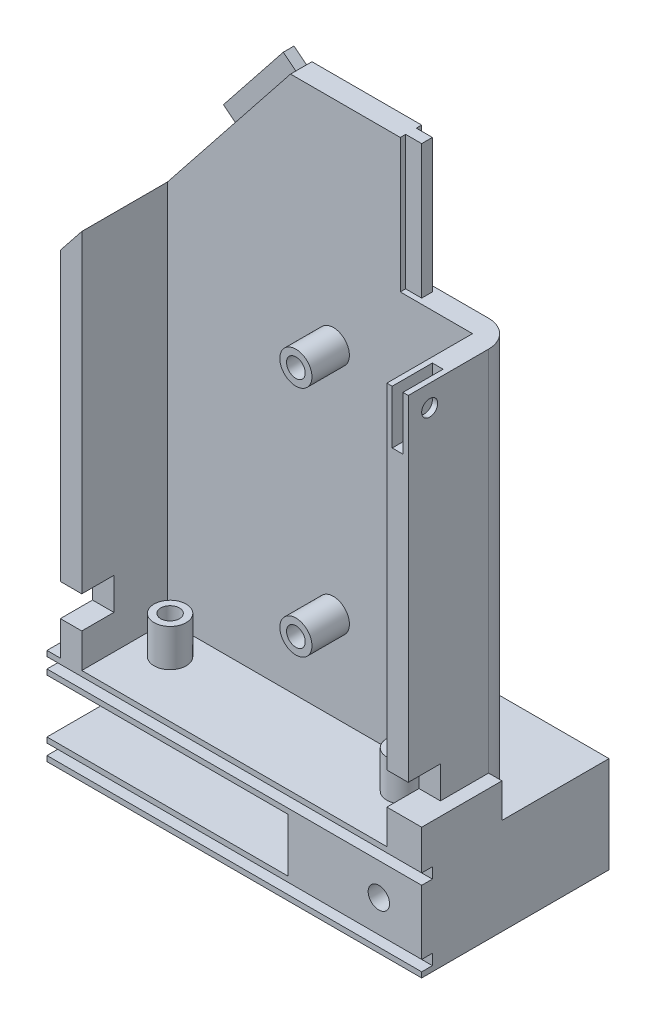
SolidWorks part; units mm, degrees
ref_plane "Front Plane" through (0, 0, 0) normal (0, 0, 1) x (1, 0, 0)
ref_plane "Top Plane" through (0, 0, 0) normal (0, 1, 0) x (1, 0, 0)
ref_plane "Right Plane" through (0, 0, 0) normal (1, 0, 0) x (0, 0, -1)
sketch "Sketch1" plane through (0, 0, 0) normal (0, 1, 0) x (1, 0, 0)
  line L1 (-32.5, -20) -> (32.5, -20)
  line L2 (-32.5, -20) -> (-32.5, 20)
  line L3 (-32.5, 20) -> (32.5, 20)
  line L4 (32.5, -20) -> (32.5, 20)
  line L5 (-32.5, -20) -> (32.5, 20) construction
  line L6 (-32.5, 20) -> (32.5, -20) construction
  point P0 (0, 0)
  dimension "D1" = 65
  dimension "D2" = 40
extrude "Boss-Extrude1" add sketch "Sketch1" along normal blind 100
shell "Shell1" thickness 4
fillet "Fillet1" radius 5 4 edges at (32.5, 50, -20) (32.5, 50, 20) (-32.5, 50, -20) (-32.5, 50, 20)
sketch "Sketch2" plane through (0, 0, 0) normal (0, 0, 1) x (1, 0, 0)
  line L0 (-5.5, 100) -> (-32.5, 66)
  line L1 (28.5, 100) -> (-28.5, 100) construction
  line L2 (-32.5, 100) -> (-32.5, 0) construction
  line L3 (-32.5, 66) -> (-32.5, 100)
  line L4 (-32.5, 100) -> (-5.5, 100)
  dimension "D1" = 5.5
  dimension "D2" = 66
extrude "Cut-Extrude1" cut sketch "Sketch2" against normal through all both and the other way through all
sketch "Sketch3" plane through (0, 0, 0) normal (0, 0, 1) x (1, 0, 0)
  line L1 (32.5, 100) -> (15, 100)
  line L2 (32.5, 100) -> (32.5, 75)
  line L3 (32.5, 75) -> (15, 75)
  line L4 (15, 100) -> (15, 75)
  dimension "D1" = 25
  dimension "D2" = 17.5
extrude "Cut-Extrude2" cut sketch "Sketch3" against normal through all both and the other way through all
sketch "Sketch5" plane through (15, 0, 0) normal (1, 0, 0) x (0, 0, -1)
  line L0 (-18, 100) -> (-18, 75) construction
  line L1 (-16, 100) -> (-20, 100) construction
  line L2 (-16, 75) -> (-20, 75) construction
  line L4 (-19, 100) -> (-17, 100)
  line L5 (-19, 100) -> (-19, 75)
  line L6 (-19, 75) -> (-17, 75)
  line L7 (-17, 100) -> (-17, 75)
  dimension "D1" = 2
extrude "Boss-Extrude2" add sketch "Sketch5" along normal blind 3
mirror "Mirror1" about plane through (0, 0, 0) normal (0, 0, 1) of "Boss-Extrude2"
sketch "Sketch6" plane through (-52.0732, 41.3523, 0) normal (-0.7831, 0.6219, 0) x (0, 0, 1)
  line L0 (-18, 74.8907) -> (-18, 56.8907) construction
  line L1 (-20, 74.8907) -> (-16, 74.8907) construction
  line L3 (-19, 74.8907) -> (-17, 74.8907)
  line L4 (-19, 74.8907) -> (-19, 56.8907)
  line L5 (-19, 56.8907) -> (-17, 56.8907)
  line L6 (-17, 74.8907) -> (-17, 56.8907)
  dimension "D1" = 18
  dimension "D2" = 2
extrude "Boss-Extrude3" add sketch "Sketch6" along normal blind 3
mirror "Mirror2" about plane through (0, 0, 0) normal (0, 0, 1) of "Boss-Extrude3"
sketch "Sketch8" plane through (0, 0, 0) normal (0, 1, 0) x (1, 0, 0)
  line L1 (-35, -35) -> (35, -35)
  line L2 (-35, -35) -> (-35, 35)
  line L3 (-35, 35) -> (35, 35)
  line L4 (35, -35) -> (35, 35)
  line L5 (-35, -35) -> (35, 35) construction
  line L6 (-35, 35) -> (35, -35) construction
  point P0 (0, 0)
  dimension "D1" = 70
  dimension "D2" = 70
extrude "Boss-Extrude4" add sketch "Sketch8" against normal blind 18
sketch "Sketch10" plane through (-35, 0, 0) normal (-1, 0, 0) x (0, 0, 1)
  line L0 (-35, -9) -> (35, -9) construction
  line L1 (-30, -14) -> (30, -14)
  line L2 (-30, -14) -> (-30, -4)
  line L3 (-30, -4) -> (30, -4)
  line L4 (30, -14) -> (30, -4)
  line L5 (-30, -14) -> (30, -4) construction
  line L6 (-30, -4) -> (30, -14) construction
  line L7 (-35, -18) -> (-35, 0) construction
  line L8 (35, -18) -> (35, 0) construction
  line L9 (0, 0) -> (0, -18) construction
  line L10 (-35, -18) -> (35, -18) construction
  point P0 (0, -9)
  dimension "D1" = 60
  dimension "D2" = 10
extrude "Cut-Extrude4" cut sketch "Sketch10" against normal blind 45
sketch "Sketch23" plane through (0, 75, 0) normal (0, 1, 0) x (1, 0, 0)
  line L0 (0, 0) -> (32.5, 0) construction
  line L1 (29.5, 7.5) -> (31.5, 7.5)
  line L2 (29.5, 7.5) -> (29.5, -7.5)
  line L3 (29.5, -7.5) -> (31.5, -7.5)
  line L4 (31.5, 7.5) -> (31.5, -7.5)
  line L5 (32.5, 15) -> (32.5, -15) construction
  line L6 (28.5, 16) -> (28.5, -16) construction
  line L8 (30.5, 14.75) -> (30.5, -14.75) construction
  point P23 (0, 0)
  point P24 (0, 0)
  point P25 (0, 0)
  point P26 (20.5505, -14.75)
  point P27 (23.5, -14.75)
  dimension "D1" = 2
  dimension "D2" = 15
extrude "Cut-Extrude10" cut sketch "Sketch23" against normal blind 10
sketch "Sketch27" plane through (0, 0, 0) normal (0, 1, 0) x (1, 0, 0)
  line L0 (35, -35) -> (35, 35) construction
  line L1 (-35, -35) -> (35, -35)
  line L2 (-35, -35) -> (-35, 0)
  line L3 (-35, 0) -> (35, 0)
  line L4 (35, -35) -> (35, 0)
extrude "Cut-Extrude12" cut sketch "Sketch27" against normal through all both and the other way through all
sketch "Sketch29" plane through (0, 0, 0) normal (0, 0, 1) x (1, 0, 0)
  line L0 (-35, -2) -> (35, -2) construction
  line L1 (-35, -4) -> (-35, 0) construction
  line L2 (35, -18) -> (35, 0) construction
  line L3 (-35, -1) -> (35, -1)
  line L4 (-35, -1) -> (-35, -3)
  line L5 (-35, -3) -> (35, -3)
  line L6 (35, -1) -> (35, -3)
  dimension "D1" = 2
extrude "Cut-Extrude13" cut sketch "Sketch29" against normal blind 2
sketch "Sketch30" plane through (0, 0, 0) normal (0, 0, 1) x (1, 0, 0)
  line L0 (-35, -16) -> (35, -16) construction
  line L1 (-35, -18) -> (-35, -14) construction
  line L2 (35, -18) -> (35, -3) construction
  line L4 (-35, -15) -> (35, -15)
  line L5 (-35, -15) -> (-35, -17)
  line L6 (-35, -17) -> (35, -17)
  line L7 (35, -15) -> (35, -17)
  dimension "D1" = 2
extrude "Cut-Extrude14" cut sketch "Sketch30" against normal blind 2
sketch "Sketch31" plane through (0, 0, 0) normal (0, 0, 1) x (1, 0, 0)
  line L0 (35, -15) -> (35, -3) construction
  line L1 (35, -18) -> (-35, -18) construction
  circle A0 centre (27, -9) radius 2
  dimension "D1" = 4
  dimension "D2" = 8
  dimension "D3" = 9
extrude "Cut-Extrude15" cut sketch "Sketch31" against normal through all both and the other way through all
sketch "Sketch33" plane through (0, 0, -35) normal (0, 0, -1) x (-1, 0, 0)
  circle A0 centre (-27, -9) radius 4
  dimension "D1" = 8
extrude "Cut-Extrude16" cut sketch "Sketch33" against normal blind 15
sketch "Sketch34" plane through (0, 0, 0) normal (0, 1, 0) x (1, 0, 0)
  line L0 (32.5, 0) -> (35, 0) construction
  line L1 (35, 0) -> (35, 35) construction
  circle A0 centre (0, 27.5) radius 1.5
  dimension "D2" = 3
  dimension "D1" = 27.5
  dimension "D3" = 35
extrude "Cut-Extrude17" cut sketch "Sketch34" against normal through all both and the other way through all
sketch "Sketch35" plane through (0, -18, 0) normal (0, -1, 0) x (-1, 0, 0)
  circle A0 centre (0, 27.5) radius 4
  dimension "D1" = 8
extrude "Cut-Extrude18" cut sketch "Sketch35" against normal blind 2.5
sketch "Sketch39" plane through (0, 0, 0) normal (0, 1, 0) x (1, 0, 0)
  line L0 (-28.5, 0) -> (28.5, 0) construction
  line L2 (28.5, 16) -> (28.5, 0) construction
  circle A0 centre (21, 10.5) radius 3
  point P4 (0, 0)
  dimension "D1" = 6
  dimension "D2" = 10.5
  dimension "D3" = 7.5
extrude "Boss-Extrude7" add sketch "Sketch39" along normal blind 7
sketch "Sketch40" plane through (0, 7, 0) normal (0, 1, 0) x (1, 0, 0)
  circle A0 centre (21, 10.5) radius 1.75
  dimension "D1" = 3.5
extrude "Cut-Extrude20" cut sketch "Sketch40" against normal blind 4
pattern_linear "LPattern4" count 2 spacing 43.5 along (-1, 0, 0) of "Boss-Extrude7", "Cut-Extrude20"
sketch "Sketch41" plane through (32.5, 0, 0) normal (1, 0, 0) x (0, 0, -1)
  line L0 (0, 75) -> (0, 0) construction
  line L1 (6, 6.4) -> (0, 6.4)
  line L2 (6, 6.4) -> (6, 12.4)
  line L3 (6, 12.4) -> (0, 12.4)
  line L4 (0, 6.4) -> (0, 12.4)
  line L5 (0, 0) -> (15, 0) construction
  dimension "D1" = 6.4
  dimension "D2" = 6
  dimension "D3" = 6
extrude "Cut-Extrude21" cut sketch "Sketch41" against normal through all both and the other way through all
sketch "Sketch42" plane through (32.5, 0, 0) normal (1, 0, 0) x (0, 0, -1)
  line L1 (0, 6.4) -> (15, 6.4)
  line L2 (0, 6.4) -> (0, 0)
  line L3 (0, 0) -> (15, 0)
  line L4 (15, 6.4) -> (15, 0)
extrude "Boss-Extrude10" add sketch "Sketch42" along normal up to surface (2.5 mm away) up to face at (35, -9, -6.5)
sketch "Sketch43" plane through (32.5, 0, 0) normal (1, 0, 0) x (0, 0, -1)
  line L0 (0, 75) -> (0, 12.4) construction
  line L1 (15, 75) -> (0, 75) construction
  circle A0 centre (4, 71) radius 1.5
  dimension "D3" = 3
  dimension "D1" = 4
  dimension "D2" = 4
extrude "Cut-Extrude22" cut sketch "Sketch43" against normal blind 10 and the other way through all
sketch "Sketch37" plane through (0, 0, -16) normal (0, 0, 1) x (1, 0, 0)
  line L0 (-28.5, 0) -> (28.5, 0) construction
  line L1 (28.5, 75) -> (28.5, 0) construction
  circle A0 centre (23.5, 60) radius 3
  dimension "D1" = 6
  dimension "D2" = 60
  dimension "D3" = 5
extrude "Boss-Extrude6" add sketch "Sketch37" along normal blind 7
sketch "Sketch38" plane through (0, 0, -9) normal (0, 0, 1) x (1, 0, 0)
  circle A0 centre (23.5, 60) radius 1.75
  dimension "D1" = 3.5
extrude "Cut-Extrude19" cut sketch "Sketch38" against normal blind 4
pattern_linear "LPattern1" count 2 spacing 21 along (-1, 0, 0) of "Boss-Extrude6", "Cut-Extrude19"
pattern_linear "LPattern2" count 2 spacing 43.5 along (0, -1, 0) of "LPattern1", "Boss-Extrude6", "Cut-Extrude19"
